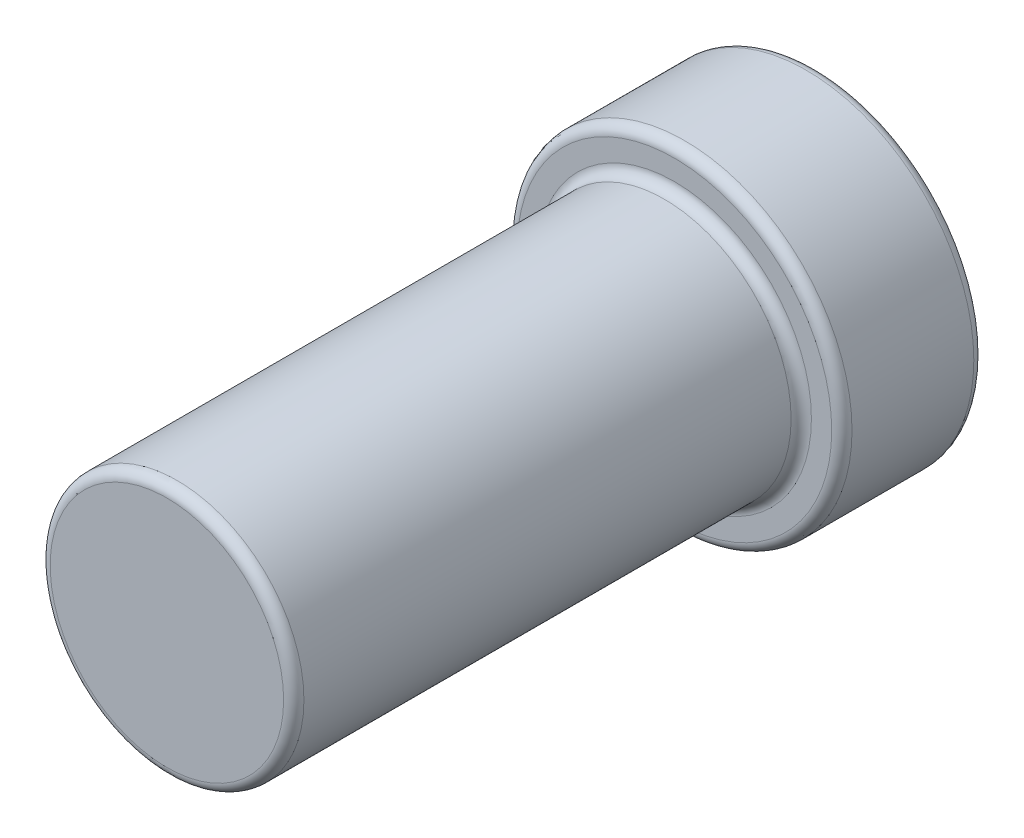
SolidWorks part; units mm, degrees
ref_plane "Front Plane" through (0, 0, 0) normal (0, 0, 1) x (1, 0, 0)
ref_plane "Top Plane" through (0, 0, 0) normal (0, 1, 0) x (1, 0, 0)
ref_plane "Right Plane" through (0, 0, 0) normal (1, 0, 0) x (0, 0, -1)
sketch "Sketch1" plane through (0, 0, 0) normal (0, 0, 1) x (1, 0, 0)
  circle A0 centre (0, 0) radius 1.65
  dimension "D1" = 3.3
extrude "Boss-Extrude1" add sketch "Sketch1" along normal blind 1.4
sketch "Sketch2" plane through (0, 0, 1.4) normal (0, 0, 1) x (1, 0, 0)
  circle A0 centre (0, 0) radius 1.25
  dimension "D1" = 2.5
extrude "Boss-Extrude2" add sketch "Sketch2" along normal blind 5
sketch "Sketch3" plane through (0, 0, 0) normal (0, 0, -1) x (-1, 0, 0)
  line L1 (1.2889, 0) -> (0.6445, 1.1163)
  line L2 (0.6445, 1.1163) -> (-0.6445, 1.1163)
  line L3 (-0.6445, 1.1163) -> (-1.2889, 0)
  line L4 (-1.2889, 0) -> (-0.6445, -1.1163)
  line L5 (-0.6445, -1.1163) -> (0.6445, -1.1163)
  line L6 (0.6445, -1.1163) -> (1.2889, 0)
  circle A0 centre (0, 0) radius 1.1163 construction
extrude "Cut-Extrude1" cut sketch "Sketch3" against normal blind 1.3
fillet "Fillet1" radius 0.1 22 edges at (0, -1.1163, 0) (0.6445, -1.1163, 0.65) (0.9667, -0.5581, 0) (1.2889, 0, 0.65) (0.9667, 0.5581, 0) (0.6445, 1.1163, 0.65) (0, 1.1163, 0) (-0.6445, 1.1163, 0.65) (-0.9667, 0.5581, 0) (-0.6445, -1.1163, 0.65) (-1.2889, 0, 0.65) (-0.9667, -0.5581, 0) (0, -1.1163, 1.3) (0.9667, -0.5581, 1.3) (0.9667, 0.5581, 1.3) (0, 1.1163, 1.3) (-0.9667, 0.5581, 1.3) (-0.9667, -0.5581, 1.3) (1.65, 0, 0) (1.65, 0, 1.4) (1.25, 0, 1.4) (1.25, 0, 6.4)
sketch "Sketch4" plane through (0, 0, 1.3) normal (0, 0, -1) x (-1, 0, 0)
  text T0 "pax" font "Dubsteptrix" height in points 2
extrude "Boss-Extrude3" add sketch "Sketch4" along normal blind 0.1
